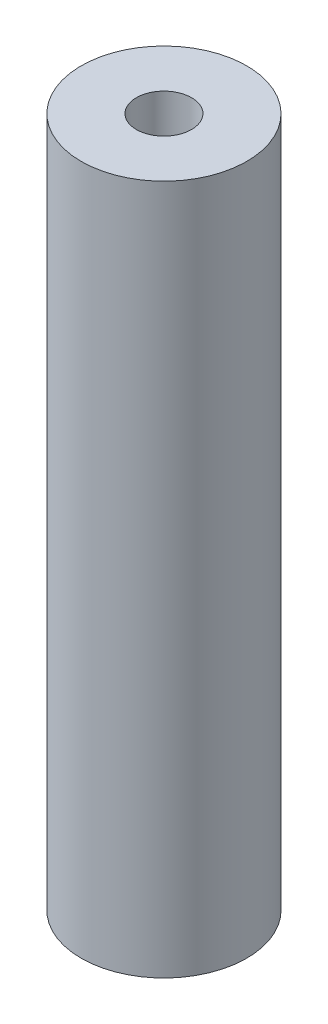
SolidWorks part; units mm, degrees
ref_plane "Přední rovina" through (0, 0, 0) normal (0, 0, 1) x (1, 0, 0)
ref_plane "Horní rovina" through (0, 0, 0) normal (0, 1, 0) x (1, 0, 0)
ref_plane "Pravá rovina" through (0, 0, 0) normal (1, 0, 0) x (0, 0, -1)
sketch "Skica1" plane through (0, 0, 0) normal (1, 0, 0) x (0, 0, -1)
  line L0 (0, 13.4683) -> (0, -11.5317) construction
  line L1 (0, 13.4683) -> (1, 13.4683) construction
  line L2 (1, 13.4683) -> (3, 13.4683)
  line L3 (3, 13.4683) -> (3, -11.5317)
  line L4 (3, -11.5317) -> (1, -11.5317)
  line L5 (1, -11.5317) -> (1, 13.4683)
  dimension "D1" = 25
  dimension "D2" = 1
  dimension "D3" = 2
  dimension "D4" = 25
revolve "Rotovat1" add sketch "Skica1" angle 360 about L0
